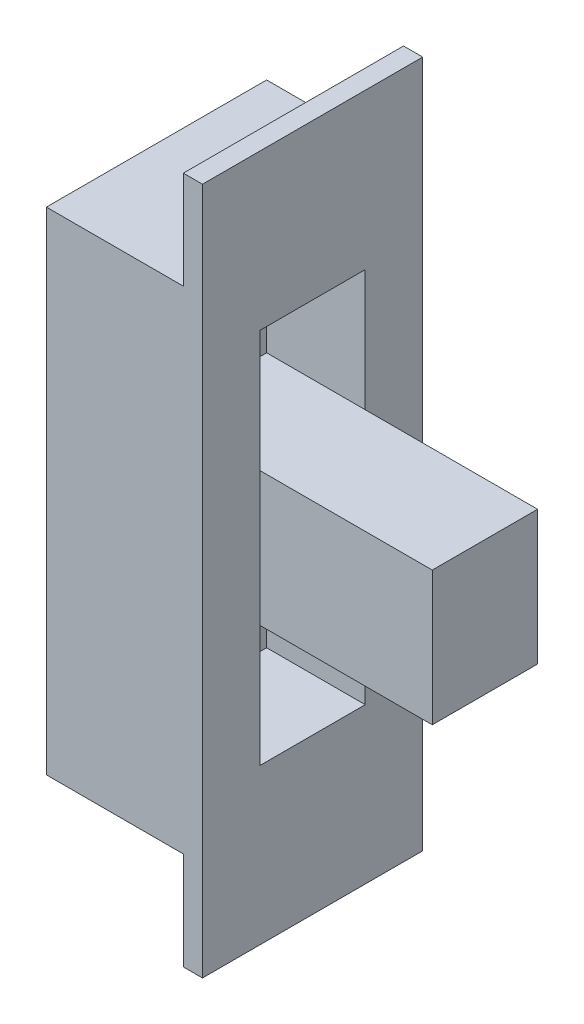
SolidWorks part; units mm, degrees
ref_plane "Plane1" through (0, 0, 0) normal (0, 0, 1) x (1, 0, 0)
ref_plane "Plane2" through (0, 0, 0) normal (0, 1, 0) x (1, 0, 0)
ref_plane "Plane3" through (0, 0, 0) normal (1, 0, 0) x (0, 0, -1)
sketch "Sketch2" plane through (0, 0, 0) normal (0, 0, 1) x (1, 0, 0)
  line L0 (-7.2426, 56.73) -> (-7.2426, 20.83)
  line L1 (-8.2426, 20.83) -> (-8.2426, 56.73)
  line L8 (-7.2426, 56.73) -> (-14.2426, 56.73) construction
  line L9 (-7.2426, 56.73) -> (-8.2426, 56.73)
  line L10 (-14.2426, 20.83) -> (-7.2426, 20.83) construction
  line L11 (-8.2426, 20.83) -> (-7.2426, 20.83)
extrude "Base-Extrude" add sketch "Sketch2" along normal blind 11.5
sketch "Sketch3" plane through (-8.2426, 0, 0) normal (-1, 0, 0) x (0, 0, 1)
  line L2 (0, 51.6191) -> (6.64, 51.6191) construction
  line L3 (0, 51.6191) -> (11.5, 51.6191)
  line L4 (0, 25.9409) -> (11.5, 25.9409)
  line L5 (0, 51.6191) -> (0, 25.9409)
  line L6 (11.5, 20.83) -> (11.5, 56.73) construction
  line L7 (11.5, 25.9409) -> (11.5, 51.6191)
extrude "Boss-Extrude1" add sketch "Sketch3" along normal blind 7.15
sketch "Sketch4" plane through (-7.2426, 0, 0) normal (1, 0, 0) x (0, 0, -1)
  line L4 (-8.5, 28.9409) -> (-8.5, 48.6191)
  line L5 (-8.5, 48.6191) -> (-3, 48.6191)
  line L6 (-3, 48.6191) -> (-3, 28.9409)
  line L7 (-3, 28.9409) -> (-8.5, 28.9409)
  line L8 (-8.5, 28.9409) -> (-8.5, 48.6191)
  line L9 (-8.5, 48.6191) -> (-3, 48.6191)
  line L10 (-3, 48.6191) -> (-3, 28.9409)
  line L11 (-3, 28.9409) -> (-8.5, 28.9409)
  dimension "D1" = 3
extrude "Cut-Extrude1" cut sketch "Sketch4" against normal offset from surface (5.15 mm away) 3 up to face at (-15.3926, 38.78, 5.75)
sketch "Sketch5" plane through (-12.3926, 0, 0) normal (1, 0, 0) x (0, 0, -1)
  line L0 (-8.5, 42.2794) -> (-3, 42.2794)
  line L1 (-8.5, 35.2794) -> (-3, 35.2794)
  line L4 (-3, 28.9409) -> (-3, 48.6191)
  line L5 (-3, 48.6191) -> (-8.5, 48.6191)
  line L6 (-8.5, 48.6191) -> (-8.5, 28.9409)
  line L7 (-8.5, 28.9409) -> (-3, 28.9409)
  line L8 (-3, 35.2794) -> (-3, 42.2794)
  line L10 (-8.5, 42.2794) -> (-8.5, 35.2794)
  dimension "D2" = 7
  dimension "D1" = 0
extrude "Boss-Extrude3" add sketch "Sketch5" along normal offset from surface (14.15 mm away) 9 up to face at (-7.2426, 38.78, 5.75) offset beyond the face yes
